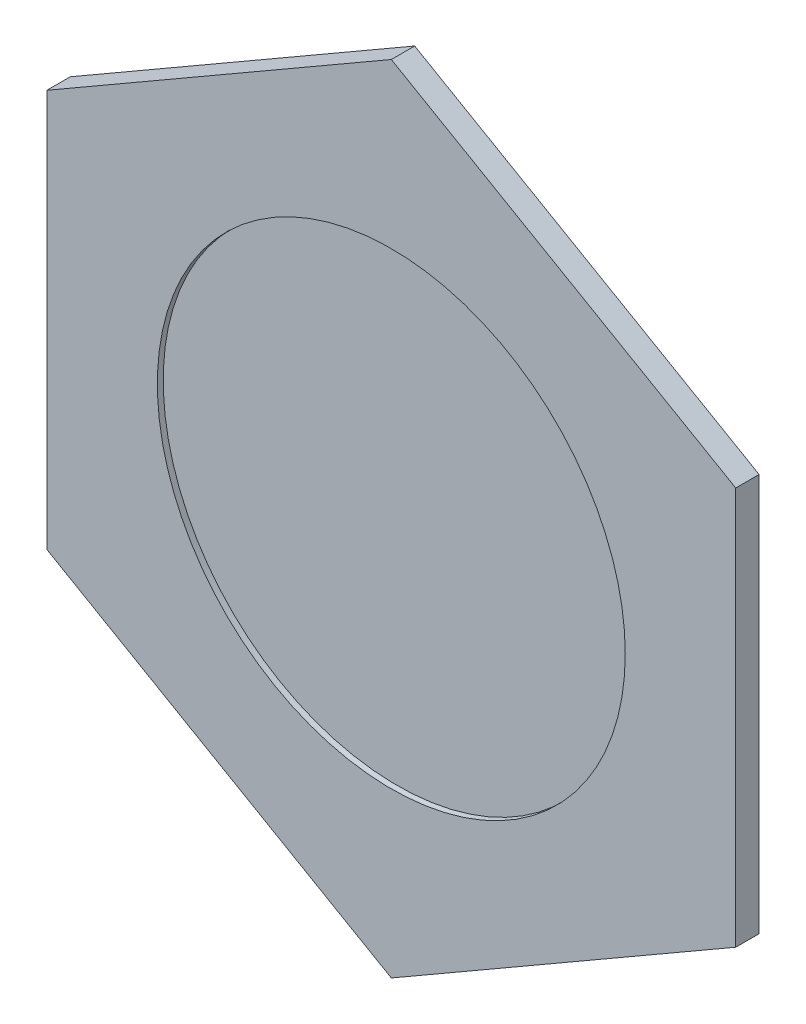
SolidWorks part; units mm, degrees
ref_plane "정면" through (0, 0, 0) normal (0, 0, 1) x (1, 0, 0)
ref_plane "윗면" through (0, 0, 0) normal (0, 1, 0) x (1, 0, 0)
ref_plane "우측면" through (0, 0, 0) normal (1, 0, 0) x (0, 0, -1)
sketch "스케치1" plane through (0, 0, 0) normal (0, 0, 1) x (1, 0, 0)
  line L0 (0, 0) -> (-56.2917, 32.5)
  line L1 (58.8897, -34) -> (58.8897, 34)
  line L2 (58.8897, 34) -> (0, 68)
  line L3 (0, 68) -> (-58.8897, 34)
  line L4 (-58.8897, 34) -> (-58.8897, -34)
  line L5 (-58.8897, -34) -> (0, -68)
  line L6 (0, -68) -> (58.8897, -34)
  line L7 (56.2917, 32.5) -> (0, 0)
  line L8 (0, -65) -> (0, 0)
  line L9 (-56.2917, 32.5) -> (-56.2917, -32.5)
  line L10 (-56.2917, -32.5) -> (0, -65)
  line L11 (0, -65) -> (56.2917, -32.5)
  line L12 (56.2917, -32.5) -> (56.2917, 32.5)
  line L13 (56.2917, 32.5) -> (0, 65)
  line L14 (0, 65) -> (-56.2917, 32.5)
  circle A1 centre (0, 0) radius 58.8897 construction
  point P1 (-58, 34.641)
  point P11 (0, -5)
  point P15 (0, -10)
  point P17 (-59, 32.909)
  point P20 (0, -15)
  point P21 (0, -20)
  point P22 (0, -25)
  point P23 (0, -30)
  point P24 (0, -35)
  point P25 (0, -40)
  point P26 (0, -45)
  point P27 (0, -50)
  point P28 (0, -55)
  point P29 (0, -60)
  point P32 (-4.3301, 2.3594)
  point P33 (-8.6603, 4.8594)
  point P34 (-12.9904, 7.3594)
  point P35 (-17.3205, 9.8594)
  point P36 (-21.6506, 12.3594)
  point P37 (-25.9808, 14.8594)
  point P38 (-30.3109, 17.3594)
  point P39 (-34.641, 19.8594)
  point P40 (-38.9711, 22.3594)
  point P41 (-43.3013, 24.8594)
  point P42 (-47.6314, 27.3594)
  point P43 (-51.9615, 29.8594)
  point P44 (4.2083, 2.4297)
  point P45 (8.5385, 4.9297)
  point P46 (12.8686, 7.4297)
  point P47 (17.1987, 9.9297)
  point P48 (21.5289, 12.4297)
  point P49 (25.859, 14.9297)
  point P50 (30.1891, 17.4297)
  point P51 (34.5192, 19.9297)
  point P52 (38.8494, 22.4297)
  point P53 (43.1795, 24.9297)
  point P54 (47.5096, 27.4297)
  point P55 (51.8397, 29.9297)
  point P56 (-0.0406, -0.0703)
  dimension "D1" = 65
  dimension "D2" = 5
  dimension "D3" = 12
  dimension "D4" = 3
  dimension "D5" = 65
  dimension "D6" = 65
  dimension "D7" = 65
  dimension "D8" = 68
extrude "보스-돌출1" add sketch "스케치1" along normal blind 4 contours L4 L5 L6 L1 L2 L3
sketch "스케치2" plane through (0, 0, 4) normal (0, 0, 1) x (1, 0, 0)
  circle A0 centre (0, 0) radius 40
  dimension "D1" = 80
extrude "컷-돌출1" cut sketch "스케치2" against normal blind 1
sketch "스케치4" plane through (0, 0, 4) normal (0, 0, 1) x (1, 0, 0)
  line L1 (0, 0) -> (-58.8897, 34)
  line L3 (-58.8897, 34) -> (-58.8897, -34)
  line L12 (-58.8897, -34) -> (0, 0)
  line L19 (-56.3897, 32.5566) -> (-56.3897, -32.5566)
  line L64 (-56.3897, -32.5566) -> (-4.3301, 2.5)
  line L65 (-51.9615, -30) -> (-8.6603, 5)
  line L66 (-47.6314, -27.5) -> (-12.9904, 7.5)
  line L67 (-43.3013, -25) -> (-17.3205, 10)
  line L68 (-38.9711, -22.5) -> (-21.6506, 12.5)
  line L69 (-34.641, -20) -> (-25.9808, 15)
  line L70 (-30.3109, -17.5) -> (-30.3109, 17.5)
  line L71 (-25.9808, -15) -> (-34.641, 20)
  line L72 (-21.6506, -12.5) -> (-38.9711, 22.5)
  line L73 (-17.3205, -10) -> (-43.3013, 25)
  line L74 (-12.9904, -7.5) -> (-47.6314, 27.5)
  line L75 (-8.6603, -5) -> (-51.9615, 30)
  line L76 (-4.3301, -2.5) -> (-56.3897, 32.5566)
  line L77 (-56.3897, 32.5566) -> (-51.9615, -30)
  line L78 (-56.3897, 27.4434) -> (-47.6314, -27.5)
  line L79 (-56.3897, 22.4434) -> (-43.3013, -25)
  line L80 (-56.3897, 17.4434) -> (-38.9711, -22.5)
  line L81 (-56.3897, 12.4434) -> (-34.641, -20)
  line L82 (-56.3897, 7.4434) -> (-30.3109, -17.5)
  line L83 (-56.3897, 2.4434) -> (-25.9808, -15)
  line L84 (-56.3897, -2.5566) -> (-21.6506, -12.5)
  line L85 (-56.3897, -7.5566) -> (-17.3205, -10)
  line L86 (-56.3897, -12.5566) -> (-12.9904, -7.5)
  line L87 (-56.3897, -17.5566) -> (-8.6603, -5)
  line L88 (-56.3897, -22.5566) -> (-4.3301, -2.5)
  line L89 (-56.3897, -27.5566) -> (0, 0)
  line L90 (-56.3897, 27.5566) -> (0, 0)
  line L91 (-56.3897, 22.5566) -> (-4.3301, 2.5)
  line L92 (-56.3897, 17.5566) -> (-8.6603, 5)
  line L93 (-56.3897, 12.5566) -> (-12.9904, 7.5)
  line L94 (-56.3897, 7.5566) -> (-17.3205, 10)
  line L95 (-56.3897, 2.5566) -> (-21.6506, 12.5)
  line L96 (-56.3897, -2.4434) -> (-25.9808, 15)
  line L97 (-56.3897, -7.4434) -> (-30.3109, 17.5)
  line L98 (-56.3897, -12.4434) -> (-34.641, 20)
  line L99 (-56.3897, -17.4434) -> (-38.9711, 22.5)
  line L100 (-56.3897, -22.4434) -> (-43.3013, 25)
  line L101 (-56.3897, -27.4434) -> (-47.6314, 27.5)
  line L102 (-56.3897, -32.5566) -> (-51.9615, 30)
  point P1 (0, -60)
  point P4 (52.0596, -35.0566)
  point P7 (56.3897, 27.5566)
  point P11 (4.3301, 62.6132)
  point P13 (8.6603, 60.1132)
  point P15 (-52.0596, 35.0566)
  point P16 (0, -55)
  point P18 (4.3301, 2.5)
  point P19 (-47.7295, 37.5566)
  point P20 (-43.3993, 40.0566)
  point P21 (56.3897, -12.4434)
  point P22 (4.3301, 2.5)
  point P23 (47.7295, -37.5566)
  point P24 (0, 10)
  point P25 (0, -50)
  point P26 (0, 15)
  point P28 (0, 45)
  point P29 (0, 25)
  point P30 (0, 30)
  point P31 (0, 0)
  point P32 (43.3013, 25)
  point P33 (0, 40)
  point P34 (-39.0692, 42.5566)
  point P35 (-34.7391, 45.0566)
  point P36 (-30.409, 47.5566)
  point P37 (-26.0788, 50.0566)
  point P38 (56.3897, 12.5566)
  point P39 (0, 20)
  point P40 (0, 15)
  point P41 (0, 10)
  point P42 (0, 5)
  point P43 (0, 20)
  point P44 (0, 15)
  point P45 (0, 10)
  point P46 (0, 5)
  point P47 (0, 20)
  point P48 (12.9904, 57.6132)
  point P49 (17.3205, 55.1132)
  point P50 (17.4186, -55.0566)
  point P51 (43.3993, -40.0566)
  point P52 (39.0692, -42.5566)
  point P53 (34.7391, -45.0566)
  point P54 (30.409, -47.5566)
  point P55 (26.0788, -50.0566)
  point P56 (21.7487, -52.5566)
  point P57 (13.0885, -57.5566)
  point P58 (8.7583, -60.0566)
  point P59 (4.4282, -62.5566)
  point P60 (0, -45)
  point P61 (0, -40)
  point P67 (0, -25)
  point P68 (0, -20)
  point P69 (0, -15)
  point P70 (0, -10)
  point P71 (0, -5)
  point P74 (-4.3301, -2.5)
  point P75 (-8.6603, -5)
  point P76 (-12.9904, -7.5)
  point P77 (-17.3205, -10)
  point P78 (-21.6506, -12.5)
  point P79 (-25.9808, -15)
  point P80 (-30.3109, -17.5)
  point P81 (-34.641, -20)
  point P82 (-38.9711, -22.5)
  point P83 (-43.3013, -25)
  point P84 (-47.6314, -27.5)
  point P85 (-51.9615, -30)
  point P86 (-4.3301, 2.5)
  point P87 (-8.6603, 5)
  point P88 (-12.9904, 7.5)
  point P89 (-17.3205, 10)
  point P90 (-21.6506, 12.5)
  point P91 (-25.9808, 15)
  point P92 (-30.3109, 17.5)
  point P93 (-34.641, 20)
  point P94 (-38.9711, 22.5)
  point P95 (-43.3013, 25)
  point P96 (-47.6314, 27.5)
  point P97 (-51.9615, 30)
  point P98 (0, 0)
  point P99 (51.9615, -30)
  point P100 (47.6314, -27.5)
  point P101 (43.3013, -25)
  point P102 (38.9711, -22.5)
  point P103 (34.641, -20)
  point P104 (30.3109, -17.5)
  point P105 (25.9808, -15)
  point P106 (21.6506, -12.5)
  point P107 (21.6506, 52.6132)
  point P108 (0, -35)
  point P109 (0, -30)
  point P110 (51.9615, 35.1132)
  point P111 (56.3897, 7.5566)
  point P112 (47.6314, 37.6132)
  point P113 (34.641, 45.1132)
  point P114 (17.3205, -10)
  point P115 (25.9808, 50.1132)
  point P116 (21.6506, 52.6132)
  point P117 (17.3205, 55.1132)
  point P118 (12.9904, 57.6132)
  point P119 (8.6603, 60.1132)
  point P120 (30.3109, 47.6132)
  point P124 (56.3897, 22.5566)
  point P125 (56.3897, -7.4434)
  point P126 (56.3897, -2.4434)
  point P127 (56.3897, 2.5566)
  point P128 (56.3897, 7.5566)
  point P129 (38.9711, 42.6132)
  point P130 (56.3897, 17.5566)
  point P131 (56.3897, 22.5566)
  point P132 (56.3897, 12.5566)
  point P155 (-4.3301, -62.6132)
  point P157 (-56.3897, 27.4434)
  point P158 (-56.3897, 22.4434)
  point P159 (-56.3897, 17.4434)
  point P160 (-56.3897, 7.4434)
  point P161 (-56.3897, 2.4434)
  point P162 (-56.3897, -2.5566)
  point P163 (-56.3897, -7.5566)
  point P164 (-56.3897, -12.5566)
  point P165 (-56.3897, -17.5566)
  point P166 (-56.3897, -22.5566)
  point P167 (-56.3897, -27.5566)
  point P168 (-56.3897, 12.4434)
  point P169 (0, 0)
  point P204 (38.9711, 22.5)
  point P217 (34.641, 20)
  point P218 (30.3109, 17.5)
  point P219 (25.9808, 15)
  point P222 (0, 0)
  point P223 (-4.3301, -2.5)
  point P224 (-8.6603, -5)
  point P225 (-12.9904, -7.5)
  point P226 (-17.3205, -10)
  point P227 (-21.6506, -12.5)
  point P228 (-25.9808, -15)
  point P229 (-30.3109, -17.5)
  point P230 (-34.641, -20)
  point P231 (-38.9711, -22.5)
  point P232 (-43.3013, -25)
  point P233 (-47.6314, -27.5)
  point P234 (-51.9615, -30)
  point P235 (-4.3301, 2.5)
  point P236 (-8.6603, 5)
  point P237 (-12.9904, 7.5)
  point P238 (-17.3205, 10)
  point P239 (-21.6506, 12.5)
  point P240 (-25.9808, 15)
  point P241 (-30.3109, 17.5)
  point P242 (-34.641, 20)
  point P243 (-38.9711, 22.5)
  point P244 (-43.3013, 25)
  point P245 (-47.6314, 27.5)
  point P246 (-51.9615, 30)
  point P247 (0, 0)
  point P250 (-56.3897, 27.4434)
  point P251 (-56.3897, 22.4434)
  point P252 (-56.3897, 17.4434)
  point P253 (-56.3897, 7.4434)
  point P254 (-56.3897, 2.4434)
  point P255 (-56.3897, -2.5566)
  point P256 (-56.3897, -7.5566)
  point P257 (-56.3897, -12.5566)
  point P258 (-56.3897, -17.5566)
  point P259 (-56.3897, -22.5566)
  point P260 (-56.3897, -27.5566)
  point P261 (-56.3897, 12.4434)
  point P262 (0, 0)
  point P309 (25.9808, 50.1132)
  point P310 (21.6506, 12.5)
  point P311 (0, 0)
  point P312 (-4.3301, 2.5)
  point P313 (-8.6603, 5)
  point P314 (-12.9904, 7.5)
  point P315 (-17.3205, 10)
  point P316 (-21.6506, 12.5)
  point P317 (-25.9808, 15)
  point P318 (-30.3109, 17.5)
  point P319 (-34.641, 20)
  point P320 (-38.9711, 22.5)
  point P321 (-43.3013, 25)
  point P322 (-47.6314, 27.5)
  point P323 (-51.9615, 30)
  point P324 (56.3897, 2.5566)
  point P325 (56.3897, -2.4434)
  point P326 (56.3897, -7.4434)
  point P327 (56.3897, -12.4434)
  point P328 (0, 35)
  point P329 (0, 25)
  point P330 (0, 30)
  point P331 (0, 45)
  point P332 (0, 40)
  point P333 (4.3301, 62.6132)
  point P334 (0, 50)
  point P335 (0, 55)
  point P336 (0, 0)
  point P338 (56.3897, 17.5566)
  point P339 (0, 60)
  point P340 (-4.4282, 62.5566)
  point P341 (-8.7583, 60.0566)
  point P342 (-13.0885, 57.5566)
  point P343 (12.9904, -7.5)
  point P344 (8.6603, -5)
  point P345 (4.3301, -2.5)
  point P346 (56.3897, -17.4434)
  point P347 (56.3897, -22.4434)
  point P348 (56.3897, -27.4434)
  point P349 (51.9615, -30)
  point P350 (-21.7487, 52.5566)
  point P351 (0, 0)
  point P352 (51.9615, 30)
  point P354 (47.6314, 27.5)
  point P356 (38.9711, 42.6132)
  point P358 (0, 35)
  point P360 (30.3109, 47.6132)
  point P362 (0, 30)
  point P364 (0, 40)
  point P366 (0, 45)
  point P368 (17.3205, 10)
  point P370 (12.9904, 7.5)
  point P372 (0, 60)
  point P374 (8.6603, 5)
  point P375 (43.3013, 40.1132)
  point P376 (43.3013, 25)
  point P377 (38.9711, 22.5)
  point P378 (34.641, 20)
  point P379 (30.3109, 17.5)
  point P380 (25.9808, 15)
  point P381 (21.6506, 12.5)
  point P382 (17.3205, 10)
  point P383 (12.9904, 7.5)
  point P384 (47.6314, -27.5)
  point P385 (8.6603, 5)
  point P386 (43.3013, 40.1132)
  point P387 (34.641, 45.1132)
  point P388 (47.6314, 37.6132)
  point P389 (51.9615, 35.1132)
  point P390 (51.9615, 30)
  point P391 (47.6314, 27.5)
  point P392 (56.3897, 27.5566)
  point P393 (0, 55)
  point P394 (0, 50)
  point P395 (-17.4186, 55.0566)
  point P396 (43.3013, -25)
  point P397 (38.9711, -22.5)
  point P398 (34.641, -20)
  point P399 (30.3109, -17.5)
  point P400 (0, 0)
  point P401 (25.9808, -15)
  point P402 (21.6506, -12.5)
  point P403 (17.3205, -10)
  point P404 (12.9904, -7.5)
  point P405 (0, 35)
  point P406 (0, 25)
  point P407 (8.6603, -5)
  point P408 (4.3301, -2.5)
  point P425 (0, 0)
  point P440 (0, 0)
  point P489 (0, 0)
  point P514 (0, 0)
  point P529 (0, 0)
  point P578 (0, 0)
  point P603 (0, 0)
  point P618 (0, 0)
  point P665 (0, 0)
  dimension "D7" = 6
